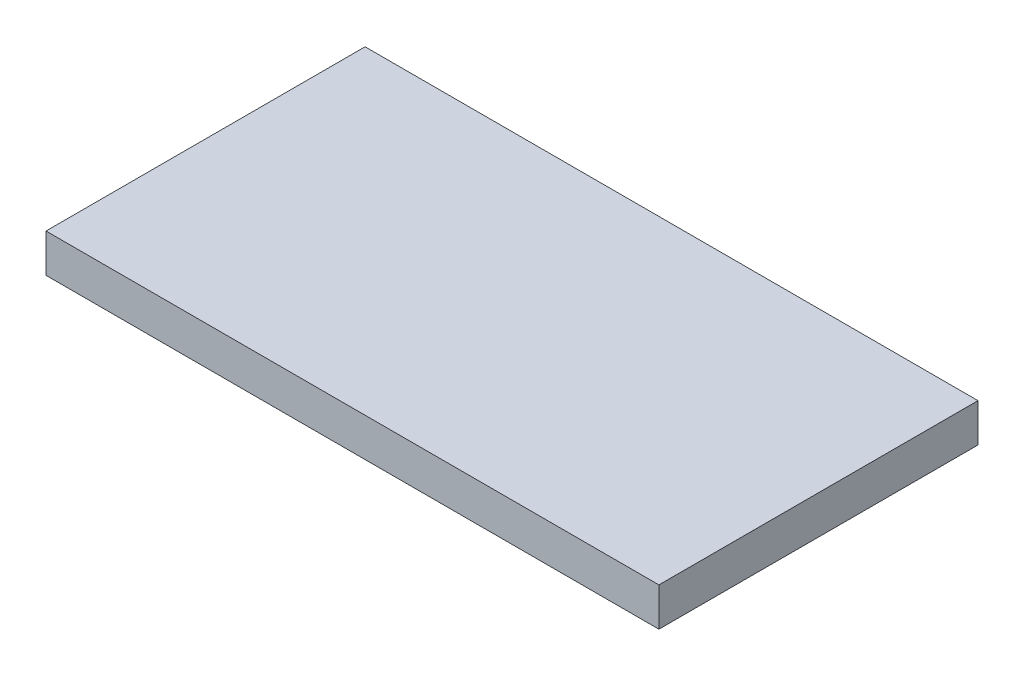
SolidWorks part; units mm, degrees
ref_plane "Front Plane" through (0, 0, 0) normal (0, 0, 1) x (1, 0, 0)
ref_plane "Top Plane" through (0, 0, 0) normal (0, 1, 0) x (1, 0, 0)
ref_plane "Right Plane" through (0, 0, 0) normal (1, 0, 0) x (0, 0, -1)
sketch "Sketch1" plane through (0, 0, 0) normal (0, 1, 0) x (1, 0, 0)
  line L0 (-314.2033, -21.01) -> (-618.2082, -21.01) construction
  line L1 (-60.2033, -21.01) -> (243.8016, -21.01)
  line L2 (-60.2033, -21.01) -> (-60.2033, 137.2574)
  line L3 (-60.2033, 137.2574) -> (243.8016, 137.2574)
  line L4 (243.8016, -21.01) -> (243.8016, 137.2574)
  line L5 (-314.2033, 137.2574) -> (-314.2033, -21.01) construction
extrude "Boss-Extrude1" add sketch "Sketch1" along normal blind 19.05
ref_plane "Left 0.02\" Offset" through (-59.6953, 0, 0) normal (1, 0, 0) x (0, 0, -1)
ref_plane "Right 0.02\" Offset" through (243.2936, 0, 0) normal (-1, 0, 0) x (0, 0, 1)
ref_plane "Midplane" through (0, 9.525, 0) normal (0, 1, 0) x (1, 0, 0)
ref_plane "Top 0.02\" Offset" through (0, 0, -136.7494) normal (0, 0, -1) x (-1, 0, 0)
